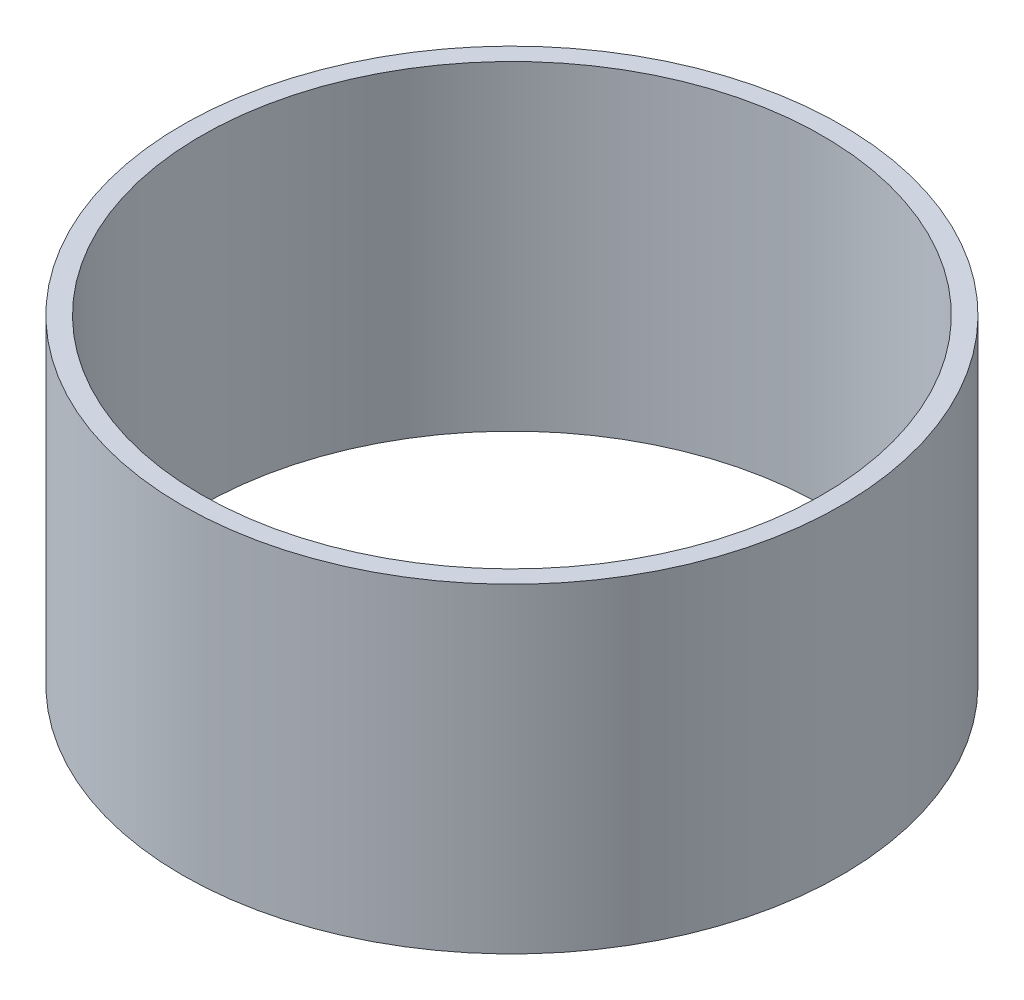
SolidWorks part; units mm, degrees
ref_plane "Front Plane" through (0, 0, 0) normal (0, 0, 1) x (1, 0, 0)
ref_plane "Top Plane" through (0, 0, 0) normal (0, 1, 0) x (1, 0, 0)
ref_plane "Right Plane" through (0, 0, 0) normal (1, 0, 0) x (0, 0, -1)
sketch "Sketch1" plane through (0, 0, 0) normal (0, 1, 0) x (1, 0, 0)
  circle A0 centre (0, 0) radius 17.5
  circle A1 centre (0, 0) radius 16.5
  dimension "D1" = 35
  dimension "D2" = 33
extrude "Boss-Extrude1" add sketch "Sketch1" along normal blind 17
